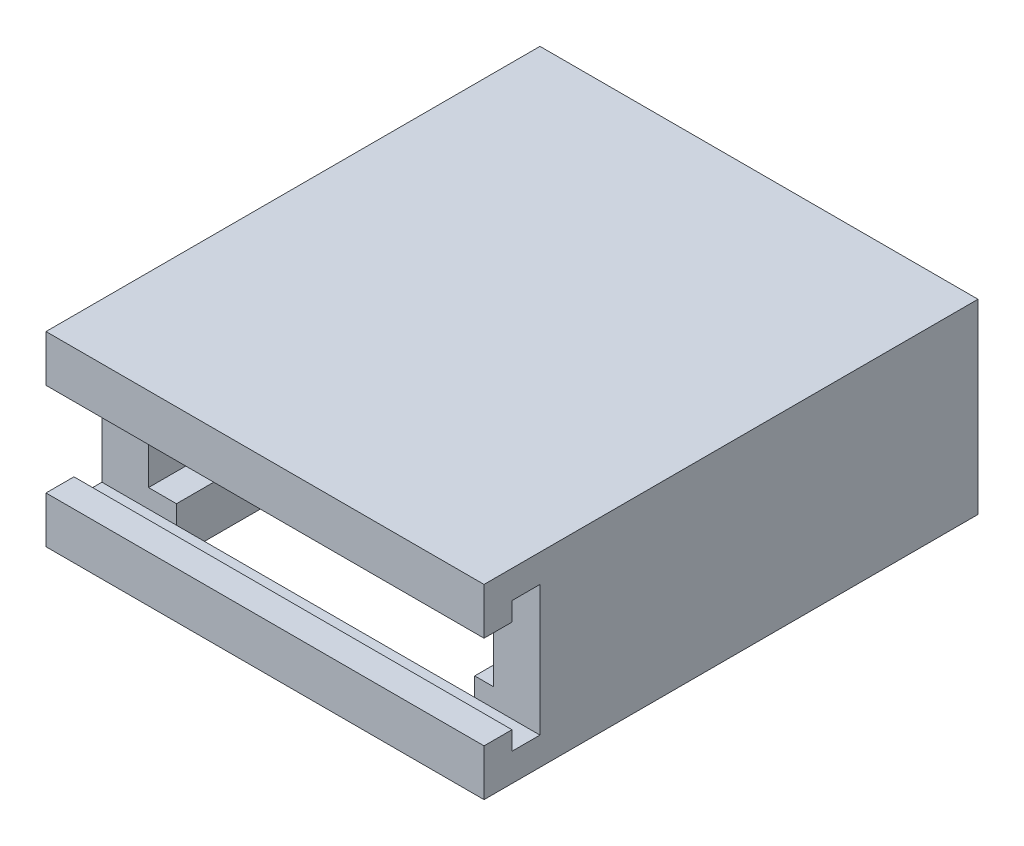
SolidWorks part; units mm, degrees
ref_plane "정면" through (0, 0, 0) normal (0, 0, 1) x (1, 0, 0)
ref_plane "윗면" through (0, 0, 0) normal (0, 1, 0) x (1, 0, 0)
ref_plane "우측면" through (0, 0, 0) normal (1, 0, 0) x (0, 0, -1)
sketch "스케치1" plane through (0, 0, 0) normal (0, 0, 1) x (1, 0, 0)
  line L1 (0, 0) -> (37, 0)
  line L2 (0, 0) -> (0, 10)
  line L3 (0, 10) -> (37, 10)
  line L4 (37, 0) -> (37, 10)
  line L5 (-5, 0) -> (42, 0)
  line L6 (-5, 0) -> (-5, 15)
  line L7 (-5, 15) -> (42, 15)
  line L8 (42, 0) -> (42, 15)
  point P9 (-5, 15)
  point P10 (0, 0)
  dimension "D1" = 37
  dimension "D2" = 10
  dimension "D3" = 5
  dimension "D4" = 5
  dimension "D5" = 15
extrude "보스-돌출1" add sketch "스케치1" along normal blind 42 contours L5 L8 L7 L6 L2 L3 L4
sketch "스케치2" plane through (0, 0, 0) normal (0, -1, 0) x (1, 0, 0)
  line L0 (0, 0) -> (37, 0) construction
  line L1 (-5, 42) -> (3, 42)
  line L2 (-5, 42) -> (-5, 0)
  line L3 (-5, 0) -> (3, 0)
  line L4 (3, 42) -> (3, 0)
  line L5 (0, 42) -> (37, 42) construction
  line L6 (42, 0) -> (35, 0)
  line L7 (42, 0) -> (42, 42)
  line L8 (42, 42) -> (35, 42)
  line L9 (35, 0) -> (35, 42)
  dimension "D1" = 7
  dimension "D2" = 8
extrude "보스-돌출2" add sketch "스케치2" along normal blind 5
sketch "스케치3" plane through (0, 0, 0) normal (0, 0, -1) x (-1, 0, 0)
  line L1 (-42, 15) -> (5, 15)
  line L2 (-42, 15) -> (-42, -5)
  line L3 (-42, -5) -> (5, -5)
  line L4 (5, 15) -> (5, -5)
extrude "보스-돌출3" add sketch "스케치3" along normal blind 5
sketch "스케치4" plane through (-5, 0, 0) normal (-1, 0, 0) x (0, 0, 1)
  line L0 (42, 15) -> (48, 15)
  line L1 (48, 15) -> (48, 10)
  line L2 (48, 10) -> (45, 10)
  line L3 (45, 10) -> (45, 12)
  line L4 (45, 12) -> (42, 12)
  line L5 (42, -5) -> (42, 15) construction
  line L6 (42, -5) -> (48, -5)
  line L7 (48, -5) -> (48, 0)
  line L8 (48, 0) -> (45, 0)
  line L9 (45, 0) -> (45, -2)
  line L10 (45, -2) -> (42, -2)
  line L11 (42, 15) -> (42, 12)
  line L12 (42, -2) -> (42, -5)
  dimension "D1" = 2
  dimension "D2" = 3
  dimension "D3" = 6
  dimension "D4" = 3
extrude "보스-돌출4" add sketch "스케치4" against normal up to vertex (47 mm away)
